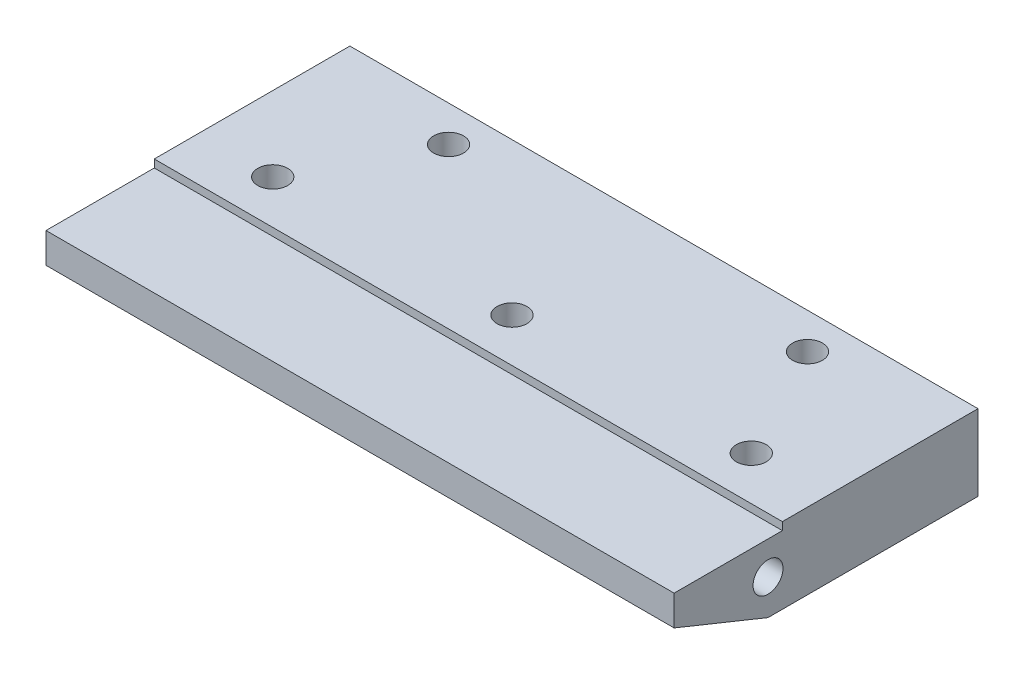
SolidWorks part; units mm, degrees
ref_plane "Alzado" through (0, 0, 0) normal (0, 0, 1) x (1, 0, 0)
ref_plane "Planta" through (0, 0, 0) normal (0, 1, 0) x (1, 0, 0)
ref_plane "Vista lateral" through (0, 0, 0) normal (1, 0, 0) x (0, 0, -1)
sketch "Croquis1" plane through (0, 0, 0) normal (0, 1, 0) x (1, 0, 0)
  line L1 (52.5, -25.4) -> (-52.5, -25.4)
  line L2 (52.5, -25.4) -> (52.5, 25.4)
  line L3 (52.5, 25.4) -> (-52.5, 25.4)
  line L4 (-52.5, -25.4) -> (-52.5, 25.4)
  line L5 (52.5, -25.4) -> (-52.5, 25.4) construction
  line L6 (52.5, 25.4) -> (-52.5, -25.4) construction
  point P0 (0, 0)
  dimension "D1" = 50.8
  dimension "D2" = 105
extrude "Saliente-Extruir1" add sketch "Croquis1" along normal blind 12.7
sketch "Croquis2" plane through (52.5, 0, 0) normal (1, 0, 0) x (0, 0, -1)
  line L0 (-25.4, 6.35) -> (-9.701, 0)
  line L1 (-25.4, 12.7) -> (-25.4, 0) construction
  line L2 (-25.4, 0) -> (25.4, 0) construction
  line L3 (-25.4, 6.35) -> (-25.4, 0)
  line L4 (-25.4, 12.7) -> (-7.3022, 12.7)
  line L5 (-25.4, 12.7) -> (-25.4, 11.3945)
  line L6 (-25.4, 11.3945) -> (-7.3022, 11.3945)
  line L7 (-7.3022, 12.7) -> (-7.3022, 11.3945)
  line L8 (-25.4, 0) -> (-9.701, 0)
extrude "Cortar-Extruir1" cut sketch "Croquis2" against normal through all
sketch "Croquis3" plane through (0, 12.7, 0) normal (0, 1, 0) x (1, 0, 0)
  line L0 (-52.5, 0) -> (52.5, 0) construction
  line L1 (52.5, -7.3022) -> (52.5, 25.4) construction
  circle A0 centre (0, 0) radius 2.5
  circle A1 centre (-40, 0) radius 2.5
  circle A2 centre (40, 0) radius 2.5
  point P6 (0, 0)
  dimension "D1" = 5
  dimension "D2" = 5
  dimension "D3" = 5
  dimension "D4" = 80
  dimension "D5" = 40
extrude "Cortar-Extruir2" cut sketch "Croquis3" against normal through all
sketch "Croquis4" plane through (0, 12.7, 0) normal (0, 1, 0) x (1, 0, 0)
  line L0 (-52.5, 19.4) -> (52.5, 19.4) construction
  line L1 (-52.5, 25.4) -> (-52.5, -7.3022) construction
  line L2 (52.5, -7.3022) -> (52.5, 25.4) construction
  line L3 (52.5, 25.4) -> (-52.5, 25.4) construction
  circle A0 centre (-30, 19.4) radius 2.5
  circle A1 centre (30, 19.4) radius 2.5
  dimension "D2" = 5
  dimension "D3" = 5
  dimension "D4" = 60
  dimension "D1" = 6
  dimension "D5" = 30
extrude "Cortar-Extruir3" cut sketch "Croquis4" against normal through all
sketch "Croquis5" plane through (52.5, 0, 0) normal (1, 0, 0) x (0, 0, -1)
  circle A0 centre (-9.701, 5.89) radius 2.5
  dimension "D1" = 5
extrude "Cortar-Extruir4" cut sketch "Croquis5" against normal blind 12
mirror "Simetría1" about plane through (0, 0, 0) normal (1, 0, 0) of "Cortar-Extruir4"
